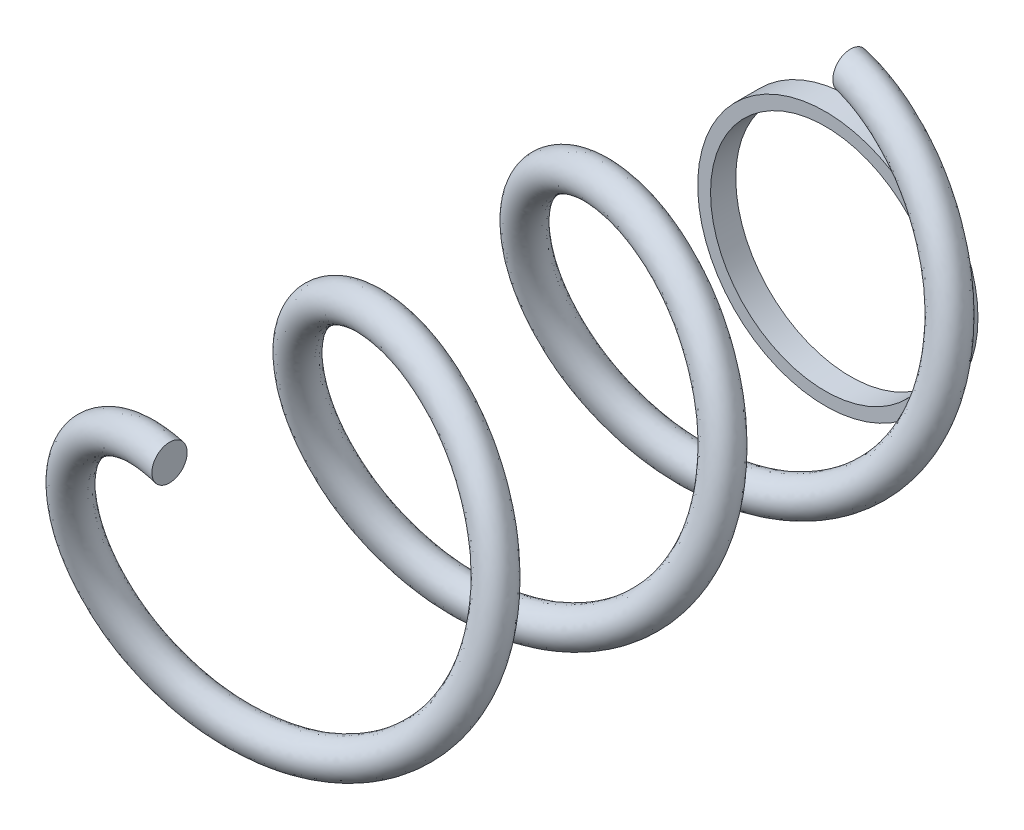
SolidWorks part; units mm, degrees
material "Cuivre"
ref_plane "Plan de face" through (0, 0, 0) normal (0, 0, 1) x (1, 0, 0)
ref_plane "Plan de dessus" through (0, 0, 0) normal (0, 1, 0) x (1, 0, 0)
ref_plane "Plan de droite" through (0, 0, 0) normal (1, 0, 0) x (0, 0, -1)
sketch "Esquisse1" plane through (0, 0, 0) normal (0, 0, 1) x (1, 0, 0)
  circle A0 centre (0, 0) radius 3
  dimension "D1" = 6
curve "Hélice/Spirale1" pitch 4.5 height 13.5 turns 3
sketch "Esquisse2" plane through (0, 0, 0) normal (1, 0, 0) x (0, 0, -1)
  circle A0 centre (0, 3) radius 0.35
  spline S0 degree 3 poles (0, 3) (-0.0932, 3) (-0.2815, 2.8438) (-0.5624, 2.1765) (-0.8438, 1.1779) (-1.125, 0) (-1.4063, -1.1779) (-1.6875, -2.1765) (-1.9688, -2.8438) (-2.25, -3.0781) (-2.5313, -2.8438) (-2.8125, -2.1765) (-3.0938, -1.1779) (-3.375, 0) (-3.6563, 1.1779) (-3.9375, 2.1765) (-4.2188, 2.8438) (-4.5, 3.0781) (-4.7813, 2.8438) (-5.0625, 2.1765) (-5.3438, 1.1779) (-5.625, 0) (-5.9063, -1.1779) (-6.1875, -2.1765) (-6.4688, -2.8438) (-6.75, -3.0781) (-7.0312, -2.8438) (-7.3125, -2.1765) (-7.5938, -1.1779) (-7.875, 0) (-8.1562, 1.1779) (-8.4375, 2.1765) (-8.7187, 2.8438) (-9, 3.0781) (-9.2812, 2.8438) (-9.5625, 2.1765) (-9.8437, 1.1779) (-10.125, 0) (-10.4062, -1.1779) (-10.6875, -2.1765) (-10.9687, -2.8438) (-11.25, -3.0781) (-11.5312, -2.8438) (-11.8125, -2.1765) (-12.0937, -1.1779) (-12.375, 0) (-12.6562, 1.1779) (-12.9376, 2.1765) (-13.2185, 2.8438) (-13.4068, 3) (-13.5, 3) knots 0 0 0 0 0.020833 0.041667 0.0625 0.083333 0.104167 0.125 0.145833 0.166667 0.1875 0.208333 0.229167 0.25 0.270833 0.291667 0.3125 0.333333 0.354167 0.375 0.395833 0.416667 0.4375 0.458333 0.479167 0.5 0.520833 0.541667 0.5625 0.583333 0.604167 0.625 0.645833 0.666667 0.6875 0.708333 0.729167 0.75 0.770833 0.791667 0.8125 0.833333 0.854167 0.875 0.895833 0.916667 0.9375 0.958333 0.979167 1 1 1 1 construction
  point P7 (0, 3)
  dimension "D1" = 0.7
sweep "Balayage1" add profiles "Esquisse2" path "Hélice/Spirale1"
sketch "Esquisse3" plane through (0, 0, 0) normal (0, 0, 1) x (1, 0, 0)
  circle A0 centre (0, 0) radius 2.5283
  circle A1 centre (0, 0) radius 2.2741
extrude "Boss.-Extru.1" add sketch "Esquisse3" along normal blind 0.5 separate body
